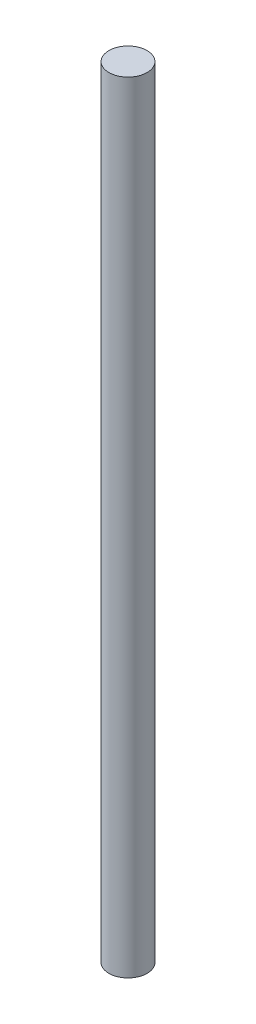
SolidWorks part; units mm, degrees
ref_plane "前视基准面" through (0, 0, 0) normal (0, 0, 1) x (1, 0, 0)
ref_plane "上视基准面" through (0, 0, 0) normal (0, 1, 0) x (1, 0, 0)
ref_plane "右视基准面" through (0, 0, 0) normal (1, 0, 0) x (0, 0, -1)
other "Configuration Table"
sketch "草图1" plane through (0, 0, 0) normal (0, 1, 0) x (1, 0, 0)
  circle A0 centre (0, 0) radius 35
  dimension "D1" = 70
extrude "凸台-拉伸1" add sketch "草图1" along normal blind 1432
